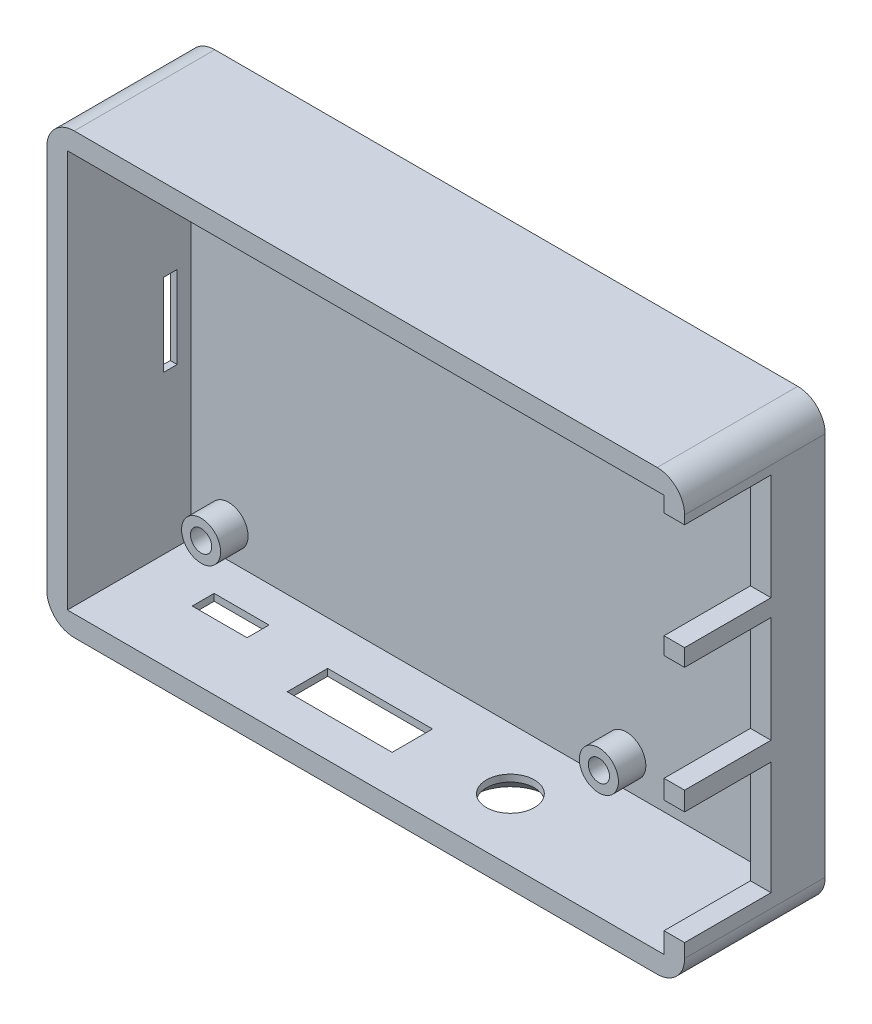
SolidWorks part; units mm, degrees
ref_plane "Přední rovina" through (0, 0, 0) normal (0, 0, 1) x (1, 0, 0)
ref_plane "Horní rovina" through (0, 0, 0) normal (0, 1, 0) x (1, 0, 0)
ref_plane "Pravá rovina" through (0, 0, 0) normal (1, 0, 0) x (0, 0, -1)
sketch "Base sketch" plane through (0, 0, 0) normal (0, 0, 1) x (1, 0, 0)
  line L1 (-43.5, 29) -> (43.5, 29)
  line L2 (-43.5, 29) -> (-43.5, -29)
  line L3 (-43.5, -29) -> (43.5, -29)
  line L4 (43.5, 29) -> (43.5, -29)
  line L5 (-43.5, 29) -> (43.5, -29) construction
  line L6 (-43.5, -29) -> (43.5, 29) construction
  line L10 (-46.5, 32) -> (46.5, 32)
  line L11 (46.5, 32) -> (46.5, -32)
  line L12 (-46.5, -32) -> (46.5, -32)
  line L13 (-46.5, 32) -> (-46.5, -32)
  point P0 (0, 0)
  dimension "D1" = 87
  dimension "D2" = 58
  dimension "D3" = 3
extrude "Base" add sketch "Base sketch" along normal blind 2.5
sketch "Walls sketch" plane through (0, 0, 2.5) normal (0, 0, 1) x (1, 0, 0)
  line L0 (-43.5, 29) -> (-43.5, -29)
  line L1 (-46.5, 32) -> (46.5, 32)
  line L2 (-46.5, 32) -> (-46.5, -32)
  line L3 (-46.5, -32) -> (46.5, -32)
  line L4 (46.5, 32) -> (46.5, -32)
  line L5 (-46.5, 32) -> (46.5, -32) construction
  line L6 (-46.5, -32) -> (46.5, 32) construction
  line L7 (-43.5, -29) -> (43.5, -29)
  line L8 (43.5, 29) -> (43.5, -29)
  line L9 (-43.5, 29) -> (43.5, 29)
  point P0 (0, 0)
  dimension "D1" = 3
extrude "Walls" add sketch "Walls sketch" along normal blind 18
sketch "Front connectors sketch" plane through (46.5, 0, 0) normal (1, 0, 0) x (0, 0, -1)
  line L0 (-7.9, -32) -> (-7.9, 32)
  line L1 (-20.5, -32) -> (0, -32) construction
  line L2 (-20.5, 32) -> (0, 32) construction
  line L3 (-20.5, -32) -> (-20.5, 32) construction
  line L4 (-7.9, -26) -> (-20.5, -26)
  line L5 (-7.9, -26) -> (-7.9, -9.5)
  line L6 (-7.9, -9.5) -> (-20.5, -9.5)
  line L7 (-20.5, -26) -> (-20.5, -9.5)
  line L9 (-7.9, 8.75) -> (-20.5, 8.75)
  line L10 (-7.9, 8.75) -> (-7.9, -6.75)
  line L11 (-7.9, -6.75) -> (-20.5, -6.75)
  line L12 (-20.5, 8.75) -> (-20.5, -6.75)
  line L13 (-7.9, 26.75) -> (-20.5, 26.75)
  line L14 (-7.9, 26.75) -> (-7.9, 11.25)
  line L15 (-7.9, 11.25) -> (-20.5, 11.25)
  line L16 (-20.5, 26.75) -> (-20.5, 11.25)
  point P21 (-20.5, -17.75)
  point P23 (-20.5, 1)
  point P24 (-20.5, 19)
  line M15 (-20.5, 32) -> (-20.5, -32)
  dimension "D1" = 7.9
  dimension "D2" = 11.25
  dimension "D3" = 16.5
  dimension "D4" = 30
  dimension "D5" = 15.5
  dimension "D6" = 48
extrude "Front connectors" cut sketch "Front connectors sketch" against normal up to next contours L0 L6 L4 M15 | L11 L0 L9 M15 | L15 L0 L13 M15
sketch "Side connectors sketch" plane through (0, -32, 0) normal (0, -1, 0) x (1, 0, 0)
  line L0 (-46.5, 7.9) -> (46.5, 7.9)
  line L1 (-46.5, 20.5) -> (-46.5, 0) construction
  line L2 (46.5, 20.5) -> (46.5, 0) construction
  line L4 (-34.9, 10.9) -> (-26.9, 10.9)
  line L5 (-34.9, 10.9) -> (-34.9, 7.7)
  line L6 (-34.9, 7.7) -> (-26.9, 7.7)
  line L7 (-26.9, 10.9) -> (-26.9, 7.7)
  line L8 (-17.15, 8.9) -> (-1.85, 8.9)
  line L9 (-17.15, 8.9) -> (-17.15, 14.8)
  line L10 (-17.15, 14.8) -> (-1.85, 14.8)
  line L11 (-1.85, 8.9) -> (-1.85, 14.8)
  circle A0 centre (12, 11.4) radius 3.5
  point P17 (-30.9, 10.9)
  point P19 (-9.5, 14.8)
  dimension "D11" = 7
  dimension "D1" = 7.9
  dimension "D2" = 3.2
  dimension "D3" = 8
  dimension "D4" = 3
  dimension "D5" = 12.6
  dimension "D6" = 55.5
  dimension "D7" = 34
  dimension "D8" = 15.3
  dimension "D9" = 5.9
  dimension "D10" = 1
  dimension "D12" = 3.5
extrude "Side connectors" cut sketch "Side connectors sketch" against normal up to next contours L6 L7 L4 L5 | L8 L11 L10 L9 | A0
chamfer "Side connectors angle" distance 2 angle 45 9 edges at (-9.5, -32, 14.8) (-17.15, -32, 11.85) (-9.5, -32, 8.9) (-1.85, -32, 11.85) (12, -32, 7.9) (-30.9, -32, 10.9) (-26.9, -32, 9.3) (-30.9, -32, 7.7) (-34.9, -32, 9.3)
sketch "SD slot sketch" plane through (-46.5, 0, 0) normal (-1, 0, 0) x (0, 0, 1)
  line L0 (0, 0) -> (20.5, 0)
  line L1 (6.5, 6) -> (4.5, 6)
  line L2 (6.5, 6) -> (6.5, -6)
  line L3 (6.5, -6) -> (4.5, -6)
  line L4 (4.5, 6) -> (4.5, -6)
  line L5 (6.5, 6) -> (4.5, -6) construction
  line L6 (6.5, -6) -> (4.5, 6) construction
  line L7 (0, 32) -> (0, -32) construction
  line L8 (20.5, 32) -> (20.5, -32) construction
  point P0 (5.5, 0)
  dimension "D1" = 6.5
  dimension "D2" = 2
  dimension "D3" = 12
extrude "SD slot" cut sketch "SD slot sketch" against normal up to next contours L4 L3 L2 L1
chamfer "SD slot angle" distance 2 angle 45 4 edges at (-46.5, 6, 5.5) (-46.5, 0, 6.5) (-46.5, -6, 5.5) (-46.5, 0, 4.5)
sketch "Mount pillar sketch" plane through (0, 0, 2.5) normal (0, 0, 1) x (1, 0, 0)
  line L1 (-38, 24.5) -> (20, 24.5)
  line L2 (-38, 24.5) -> (-38, -24.5)
  line L3 (-38, -24.5) -> (20, -24.5)
  line L4 (20, 24.5) -> (20, -24.5)
  line L5 (-38, 24.5) -> (20, -24.5) construction
  line L6 (-38, -24.5) -> (20, 24.5) construction
  circle A0 centre (-38, -24.5) radius 1.55
  circle A1 centre (-38, -24.5) radius 2.85
  circle A2 centre (20, -24.5) radius 2.85
  circle A3 centre (20, -24.5) radius 1.55
  circle A4 centre (20, 24.5) radius 2.85
  circle A5 centre (20, 24.5) radius 1.55
  circle A6 centre (-38, 24.5) radius 2.85
  circle A7 centre (-38, 24.5) radius 1.55
  point P0 (-9, 0)
  dimension "D5" = 3.1
  dimension "D6" = 5.7
  dimension "D1" = 5.5
  dimension "D2" = 49
  dimension "D3" = 58
  dimension "D4" = 4.5
  dimension "D7" = 2
  dimension "D8" = 2
extrude "Mount pillars" add sketch "Mount pillar sketch" along normal blind 4 contours A1 | A2 | A4 | A6
hole_wizard "Insert nut holes" positions "Skica8" profile "Skica10" hole size "Ø3.0" standard "ISO"
sketch "Skica8" plane through (0, 0, 6.5) normal (0, 0, 1) x (1, 0, 0)
  point P0 (-38, 24.5)
  point P3 (20, 24.5)
  point P6 (20, -24.5)
  point P9 (-38, -24.5)
sketch "Skica10" plane through (-38, 24.5, 6.5) normal (1, 0, 0) x (0, -1, 0)
  line L0 (0, 0) -> (0, 5.9313)
  line L1 (0, 5.9313) -> (1.55, 5)
  line L2 (1.55, 5) -> (1.55, 0)
  line L5 (1.55, 0) -> (0, 0)
  line L10 (0, 5.9313) -> (-1.55, 5) construction
  line L11 (0, -6.35) -> (0, 107.95) construction
  dimension "Průměr díry" = 3.1
  dimension "Hloubka díry" = 5
  dimension "Úhel vrtání" = 118
fillet "Zaoblit2" radius 4 4 edges at (46.5, 32, 10.25) (-46.5, 32, 10.25) (-46.5, -32, 10.25) (46.5, -32, 10.25)
